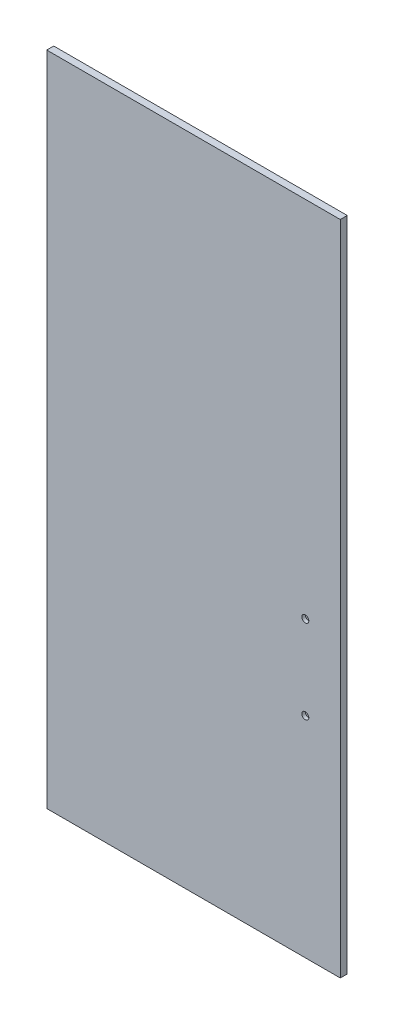
SolidWorks part; units mm, degrees
material "Бук"
ref_plane "Спереди" through (0, 0, 0) normal (0, 0, 1) x (1, 0, 0)
ref_plane "Сверху" through (0, 0, 0) normal (0, 1, 0) x (1, 0, 0)
ref_plane "Справа" through (0, 0, 0) normal (1, 0, 0) x (0, 0, -1)
sketch "Эскиз1" plane through (0, 0, 0) normal (0, 0, 1) x (1, 0, 0)
  line L1 (0, 0) -> (420, 0)
  line L2 (0, 0) -> (0, 940)
  line L3 (0, 940) -> (420, 940)
  line L4 (420, 0) -> (420, 940)
  dimension "D1" = 420
  dimension "D2" = 940
extrude "Бобышка-Вытянуть1" add sketch "Эскиз1" along normal blind 10
sketch "Эскиз2" plane through (0, 0, 10) normal (0, 0, 1) x (1, 0, 0)
  line L2 (420, 0) -> (420, 940) construction
  line L3 (370, 940) -> (370, 0) construction
  line L4 (420, 940) -> (0, 940) construction
  line L5 (0, 0) -> (420, 0) construction
  circle A0 centre (370, 420) radius 5
  circle A1 centre (370, 300) radius 5
  dimension "D2" = 10
  dimension "D3" = 10
  dimension "D1" = 50
  dimension "D4" = 300
  dimension "D5" = 120
extrude "Вырез-Вытянуть1" cut sketch "Эскиз2" against normal blind 5
